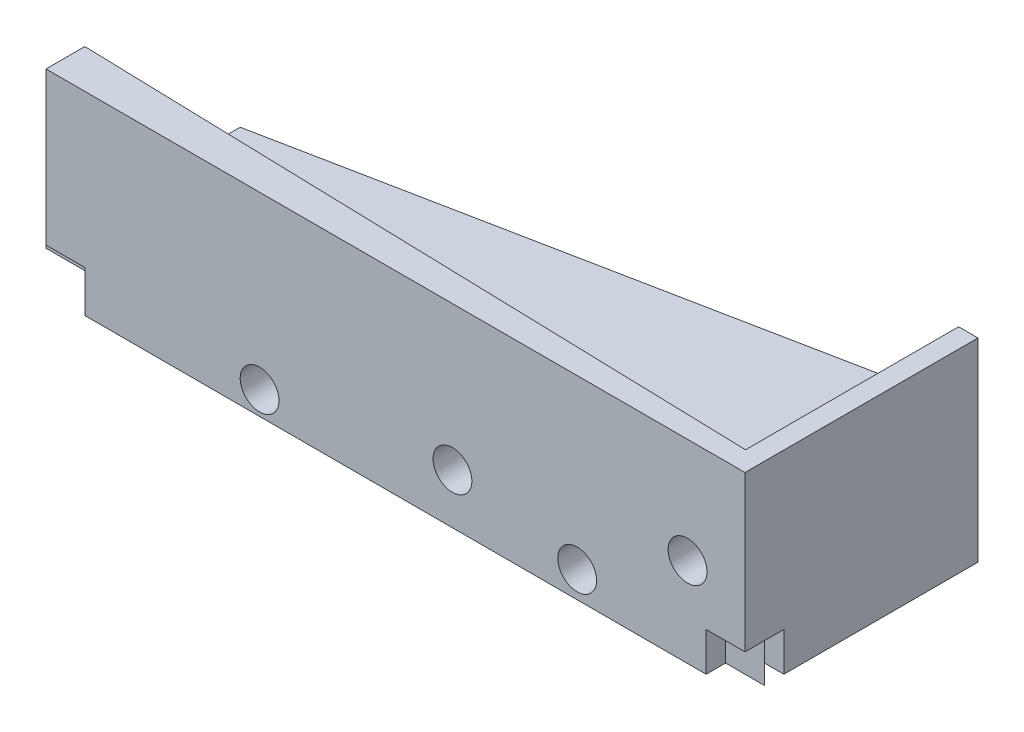
SolidWorks part; units mm, degrees
ref_plane "Plan de face" through (0, 0, 0) normal (0, 0, 1) x (1, 0, 0)
ref_plane "Plan de dessus" through (0, 0, 0) normal (0, 1, 0) x (1, 0, 0)
ref_plane "Plan de droite" through (0, 0, 0) normal (1, 0, 0) x (0, 0, -1)
sketch "Esquisse1" plane through (0, 0, 0) normal (0, 0, 1) x (1, 0, 0)
  line L0 (-105.796, 0) -> (84.204, 0)
  line L1 (84.204, 0) -> (84.204, 33.5021)
  line L2 (84.204, 25.3929) -> (-68.9493, 0) construction
  line L3 (-105.796, 0) -> (-105.796, 2)
  line L4 (-105.796, 2) -> (84.204, 33.5021)
  line L5 (40.9815, 6.7762) -> (8.8615, 12.9011) construction
  line L6 (69.406, 22.9394) -> (40.9815, 6.7762) construction
  circle A0 centre (69.406, 22.9394) radius 3
  circle A1 centre (40.9815, 6.7762) radius 3
  circle A2 centre (-40.796, 6) radius 3
  circle A3 centre (8.8615, 12.9011) radius 3
  dimension "D3" = 6
  dimension "D6" = 6
  dimension "D8" = 6
  dimension "D11" = 6
  dimension "D1" = 190
  dimension "D2" = 2
  dimension "D4" = 15
  dimension "D7" = 8
  dimension "D9" = 6
  dimension "D10" = 65
extrude "Boss.-Extru.1" add sketch "Esquisse1" along normal blind 200
sketch "Esquisse4" plane through (84.204, 0, 0) normal (1, 0, 0) x (0, 0, -1)
  line L1 (-200, 0) -> (-205, 0)
  line L2 (-200, 0) -> (-200, 50)
  line L3 (-200, 50) -> (-205, 50)
  line L4 (-205, 0) -> (-205, 50)
  line L5 (0, 0) -> (5, 0)
  line L6 (0, 0) -> (0, 50)
  line L7 (0, 50) -> (5, 50)
  line L8 (5, 0) -> (5, 50)
  dimension "D1" = 50
  dimension "D2" = 5
  dimension "D3" = 5
  dimension "D4" = 50
extrude "Boss.-Extru.4" add sketch "Esquisse4" against normal blind 180
sketch "Esquisse8" plane through (0, 50, 0) normal (0, 1, 0) x (1, 0, 0)
  line L0 (84.204, 0) -> (-95.796, 0)
  line L1 (-95.796, 0) -> (-95.796, -5)
  line L2 (-95.796, -5) -> (84.204, 0)
  dimension "D1" = 5
extrude "Boss.-Extru.7" add sketch "Esquisse8" against normal up to surface (50 mm away)
ref_plane "Plan2" through (-5.796, 0, 0) normal (1, 0, 0) x (0, 0, -1)
sketch "Esquisse6" plane through (0, 0, -5) normal (0, 0, -1) x (-1, 0, 0)
  line L1 (105.796, 0) -> (85.796, 0)
  line L2 (105.796, 0) -> (105.796, 10.7198)
  line L3 (105.796, 10.7198) -> (85.796, 10.7198)
  line L4 (85.796, 0) -> (85.796, 10.7198)
  line L5 (95.796, 0) -> (95.796, 50) construction
  dimension "D1" = 10
extrude "Enlèv. mat.-Extru.2" cut sketch "Esquisse6" against normal blind 10
ref_plane "Plan3" through (0, 0, 100) normal (0, 0, -1) x (-1, 0, 0)
sketch "Esquisse5" plane through (84.204, 0, 0) normal (1, 0, 0) x (0, 0, -1)
  line L1 (-205, 0) -> (-195, 0)
  line L2 (-205, 0) -> (-205, 10)
  line L3 (-205, 10) -> (-195, 10)
  line L4 (-195, 0) -> (-195, 10)
  line L5 (5, 0) -> (-5, 0)
  line L6 (5, 0) -> (5, 10)
  line L7 (5, 10) -> (-5, 10)
  line L8 (-5, 0) -> (-5, 10)
  dimension "D1" = 10
  dimension "D2" = 10
  dimension "D3" = 10
  dimension "D4" = 10
extrude "Enlèv. mat.-Extru.1" cut sketch "Esquisse5" against normal blind 10
sketch "Esquisse14" plane through (0, 0, -5) normal (0, 0, -1) x (-1, 0, 0)
  circle A0 centre (-69.406, 22.9394) radius 5
  circle A1 centre (-40.9815, 6.7762) radius 5
  circle A2 centre (-8.8615, 12.9011) radius 5
  circle A3 centre (40.796, 6) radius 5
  dimension "D1" = 10
  dimension "D2" = 10
  dimension "D3" = 10
  dimension "D4" = 10
extrude "Enlèv. mat.-Extru.4" cut sketch "Esquisse14" against normal blind 15
mirror "Symétrie3" about plane through (0, 0, 100) normal (0, 0, -1) of "Enlèv. mat.-Extru.4", "Boss.-Extru.7", "Enlèv. mat.-Extru.2"
sketch "Esquisse15" plane through (0, 0, -5) normal (0, 0, -1) x (-1, 0, 0)
  line L0 (-84.204, 33.5021) -> (-79.204, 32.6731)
  line L1 (-84.204, 33.5021) -> (85.796, 5.316) construction
  line L2 (-79.204, 32.6731) -> (-79.204, 50)
  line L3 (95.796, 50) -> (-84.204, 50) construction
  line L4 (-79.204, 50) -> (-84.204, 50)
  line L5 (-84.204, 50) -> (-84.204, 33.5021)
  dimension "D1" = 5
extrude "Boss.-Extru.8" add sketch "Esquisse15" against normal up to surface (204.8611 mm away)
sketch "Esquisse16" plane through (0, 50, 0) normal (0, 1, 0) x (1, 0, 0)
  line L0 (-105.796, -195) -> (-105.796, -5) construction
  line L1 (84.204, 5) -> (-105.796, 5)
  line L2 (84.204, 5) -> (84.204, -145)
  line L3 (84.204, -145) -> (-105.796, -145)
  line L4 (-105.796, 5) -> (-105.796, -145)
  line L5 (-95.796, -205) -> (84.204, -205) construction
  dimension "D1" = 60
extrude "Enlèv. mat.-Extru.5" cut sketch "Esquisse16" against normal up to surface (50 mm away) up to face at (9.5373, 0, 119.9815)
